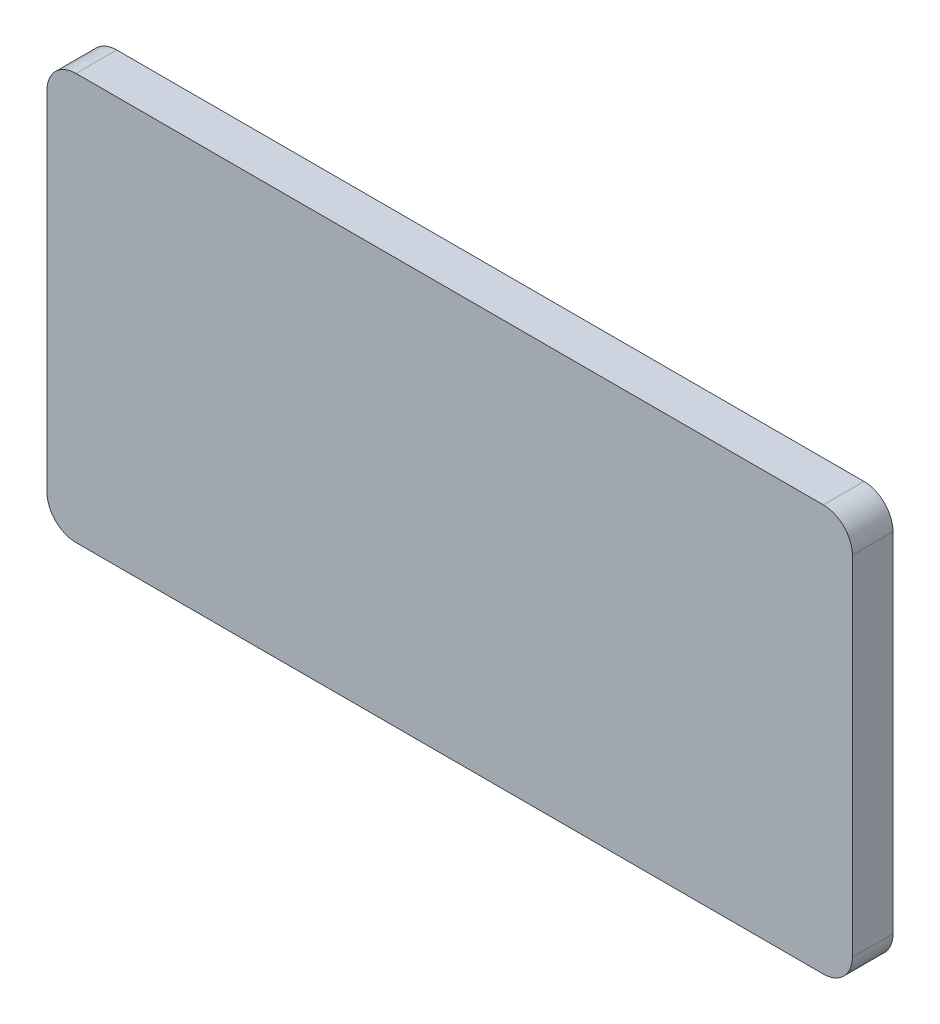
SolidWorks part; units mm, degrees
ref_plane "Front Plane" through (0, 0, 0) normal (0, 0, 1) x (1, 0, 0)
ref_plane "Top Plane" through (0, 0, 0) normal (0, 1, 0) x (1, 0, 0)
ref_plane "Right Plane" through (0, 0, 0) normal (1, 0, 0) x (0, 0, -1)
sketch "Sketch1" plane through (0, 0, 0) normal (0, 0, 1) x (1, 0, 0)
  line L1 (-65.6231, 35) -> (63.1306, 35)
  line L2 (-70.6231, 30) -> (-70.6231, -30)
  line L3 (-65.6231, -35) -> (63.1306, -35)
  line L4 (68.1306, 30) -> (68.1306, -30)
  line L5 (-70.6231, 35) -> (68.1306, -35) construction
  line L6 (-70.6231, -35) -> (68.1306, 35) construction
  arc A0 (-70.6231, -30) -> (-65.6231, -35) centre (-65.6231, -30) ccw
  arc A1 (63.1306, -35) -> (68.1306, -30) centre (63.1306, -30) ccw
  arc A2 (63.1306, 35) -> (68.1306, 30) centre (63.1306, 30) cw
  arc A3 (-65.6231, 35) -> (-70.6231, 30) centre (-65.6231, 30) ccw
  point P0 (-1.2463, 0)
  dimension "D3" = 5
  dimension "D1" = 70
  dimension "D2" = 138.7537
extrude "Boss-Extrude1" add sketch "Sketch1" along normal blind 7
